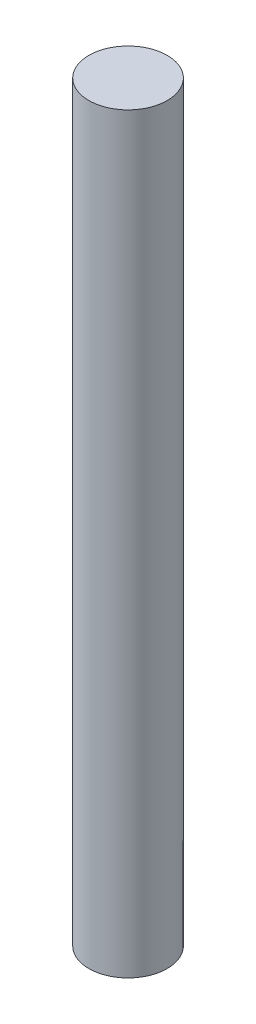
SolidWorks part; units mm, degrees
ref_plane "Front Plane" through (0, 0, 0) normal (0, 0, 1) x (1, 0, 0)
ref_plane "Top Plane" through (0, 0, 0) normal (0, 1, 0) x (1, 0, 0)
ref_plane "Right Plane" through (0, 0, 0) normal (1, 0, 0) x (0, 0, -1)
sketch "Sketch1" plane through (0, 0, 0) normal (0, 1, 0) x (1, 0, 0)
  circle A0 centre (0, 0) radius 3.9688
  dimension "D1" = 7.9375
extrude "Boss-Extrude1" add sketch "Sketch1" along normal blind 76.2
cosmetic thread "Cosmetic Thread1"
hole_wizard "#10-32 Tapped Hole1" positions "Sketch3" profile "Sketch4" tap size "#10-32" standard "ANSI Inch"
sketch "Sketch3" plane through (0, 0, 0) normal (0, -1, 0) x (-1, 0, 0)
  point P0 (0, 0)
sketch "Sketch4" plane through (0, 0, 0) normal (1, 0, 0) x (0, 0, -1)
  line L0 (0, 0) -> (0, 13.9133)
  line L1 (0, 13.9133) -> (2.0193, 12.7)
  line L2 (2.0193, 12.7) -> (2.0193, 0)
  line L5 (2.0193, 0) -> (0, 0)
  line L10 (0, 13.9133) -> (-2.0193, 12.7) construction
  line L11 (0, -6.35) -> (0, 107.95) construction
  dimension "Tap Drill Dia." = 4.0386
  dimension "Tap Drill Depth" = 12.7
  dimension "Drill Angle" = 118
cosmetic thread "Hole Thread1" parameters "D1"=9.525, "D2"=4.826
